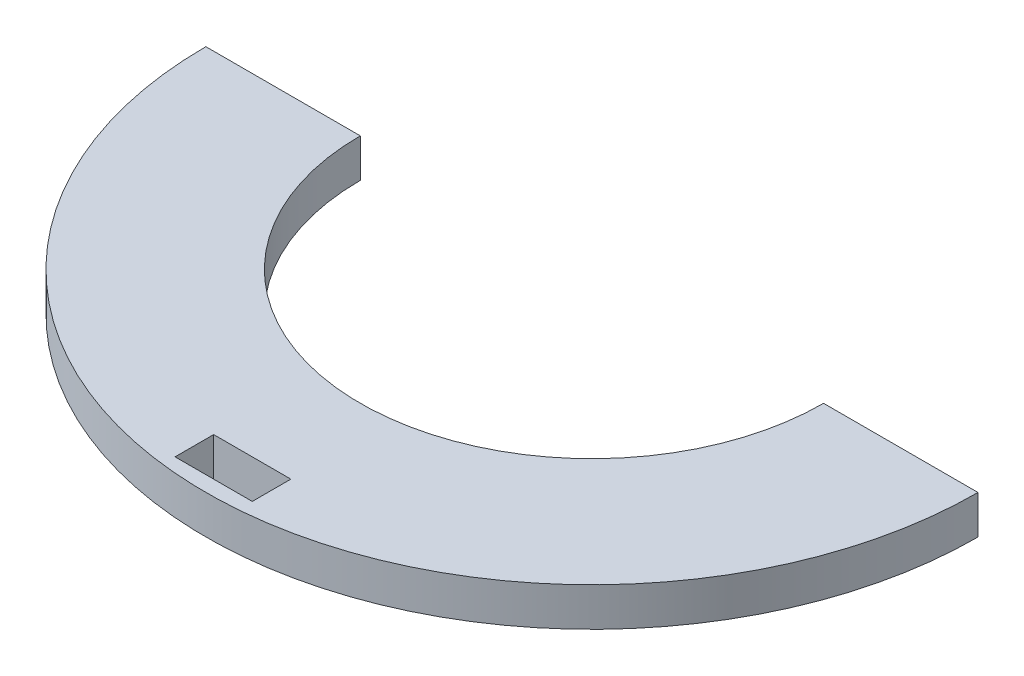
SolidWorks part; units mm, degrees
material "PE Low/Medium Density"
ref_plane "Front Plane" through (0, 0, 0) normal (0, 0, 1) x (1, 0, 0)
ref_plane "Top Plane" through (0, 0, 0) normal (0, 1, 0) x (1, 0, 0)
ref_plane "Right Plane" through (0, 0, 0) normal (1, 0, 0) x (0, 0, -1)
sketch "Sketch1" plane through (0, 0, 0) normal (0, 1, 0) x (1, 0, 0)
  line L0 (-30, 0) -> (-50, 0)
  line L1 (30, 0) -> (50, 0)
  arc A0 (-30, 0) -> (30, 0) centre (0, 0) ccw
  arc A1 (-50, 0) -> (50, 0) centre (0, 0) ccw
  dimension "D1" = 20
  dimension "D2" = 20
extrude "Boss-Extrude1" add sketch "Sketch1" along normal blind 5
sketch "Sketch2" plane through (0, 5, 0) normal (0, 1, 0) x (1, 0, 0)
  line L1 (-5.9901, -48) -> (4.0099, -48)
  line L2 (-5.9901, -48) -> (-5.9901, -43)
  line L3 (-5.9901, -43) -> (4.0099, -43)
  line L4 (4.0099, -48) -> (4.0099, -43)
  line L5 (-5.9901, -48) -> (4.0099, -43) construction
  line L6 (-5.9901, -43) -> (4.0099, -48) construction
  point P0 (-0.9901, -45.5)
  dimension "D1" = 5
  dimension "D2" = 10
  dimension "D3" = 43
extrude "Cut-Extrude2" cut sketch "Sketch2" against normal blind 10
